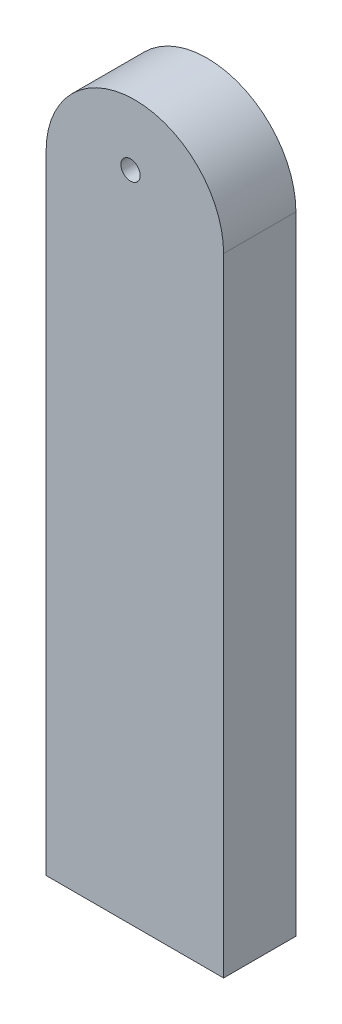
SolidWorks part; units mm, degrees
ref_plane "Plano frontal" through (0, 0, 0) normal (0, 0, 1) x (1, 0, 0)
ref_plane "Plano superior" through (0, 0, 0) normal (0, 1, 0) x (1, 0, 0)
ref_plane "Plano direito" through (0, 0, 0) normal (1, 0, 0) x (0, 0, -1)
sketch "Esboço1" plane through (0, 0, 0) normal (0, 0, 1) x (1, 0, 0)
  line L2 (-17.4936, 31.213) -> (-17.4936, -98.787)
  line L3 (-17.4936, -98.787) -> (19.2864, -98.787)
  line L4 (19.2864, 31.213) -> (19.2864, -98.787)
  arc A0 (-17.4936, 31.213) -> (19.2864, 31.213) centre (0.8964, 31.213) cw
  point P0 (0, 0)
  dimension "D1" = 130
  dimension "D2" = 36.78
  dimension "D3" = 130
  dimension "D4" = 130
extrude "Ressalto-extrusão1" add sketch "Esboço1" along normal blind 14.98
sketch "Esboço2" plane through (0, 0, 14.98) normal (0, 0, 1) x (1, 0, 0)
  circle A0 centre (0, 36.5622) radius 2
extrude "Corte-extrusão1" cut sketch "Esboço2" against normal mid plane 125
